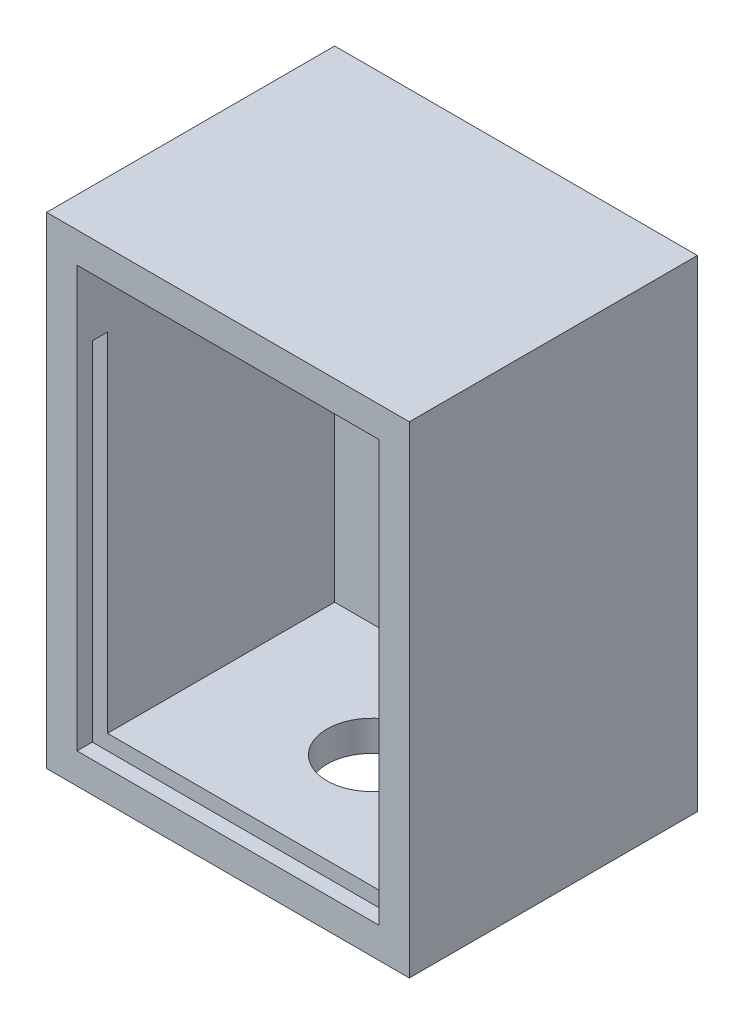
SolidWorks part; units mm, degrees
ref_plane "Front Plane" through (0, 0, 0) normal (0, 0, 1) x (1, 0, 0)
ref_plane "Top Plane" through (0, 0, 0) normal (0, 1, 0) x (1, 0, 0)
ref_plane "Right Plane" through (0, 0, 0) normal (1, 0, 0) x (0, 0, -1)
sketch "Sketch2" plane through (-2.1621, 0, 0) normal (0, 1, 0) x (1, 0, 0)
  line L0 (-94.6172, -8.79) -> (-92.6172, -8.79) construction
  line L1 (-94.6172, -8.79) -> (-70.8172, -8.79)
  line L2 (-94.6172, -8.79) -> (-94.6172, -27.69)
  line L3 (-94.6172, -27.69) -> (-70.8172, -27.69)
  line L4 (-70.8172, -8.79) -> (-70.8172, -27.69)
  line L10 (-70.8172, -8.79) -> (-72.8172, -8.79) construction
  line L13 (-94.6172, -27.69) -> (-92.6172, -27.69) construction
  line L14 (-70.8172, -27.69) -> (-72.8172, -27.69) construction
  line L17 (-92.6172, -10.79) -> (-72.8172, -10.79)
  line L18 (-92.6172, -10.79) -> (-92.6172, -25.69)
  line L19 (-92.6172, -25.69) -> (-72.8172, -25.69)
  line L20 (-72.8172, -10.79) -> (-72.8172, -25.69)
extrude "Boss-Extrude1" add sketch "Sketch2" along normal blind 31.6 contours L1 L4 L3 L2
shell "Shell2" thickness 2
sketch "Sketch10" plane through (0, 0, 0) normal (0, -1, 0) x (1, 0, 0)
  line L1 (-96.7793, 27.69) -> (-72.9793, 27.69) construction
  line L2 (-72.9793, 27.69) -> (-73.9793, 27.69) construction
  line L6 (-95.8385, 26.69) -> (-74.0385, 26.69)
  line L7 (-95.8385, 26.69) -> (-95.8385, 25.69)
  line L8 (-95.8385, 25.69) -> (-74.0385, 25.69)
  line L9 (-74.0385, 26.69) -> (-74.0385, 25.69)
extrude "Cut-Extrude5" cut sketch "Sketch10" against normal blind 24.8
sketch "Sketch12" plane through (0, 0, 0) normal (0, -1, 0) x (-1, 0, 0)
  circle A0 centre (84.8793, -18.24) radius 2.95
extrude "Cut-Extrude6" cut sketch "Sketch12" against normal blind 2 contours A0
